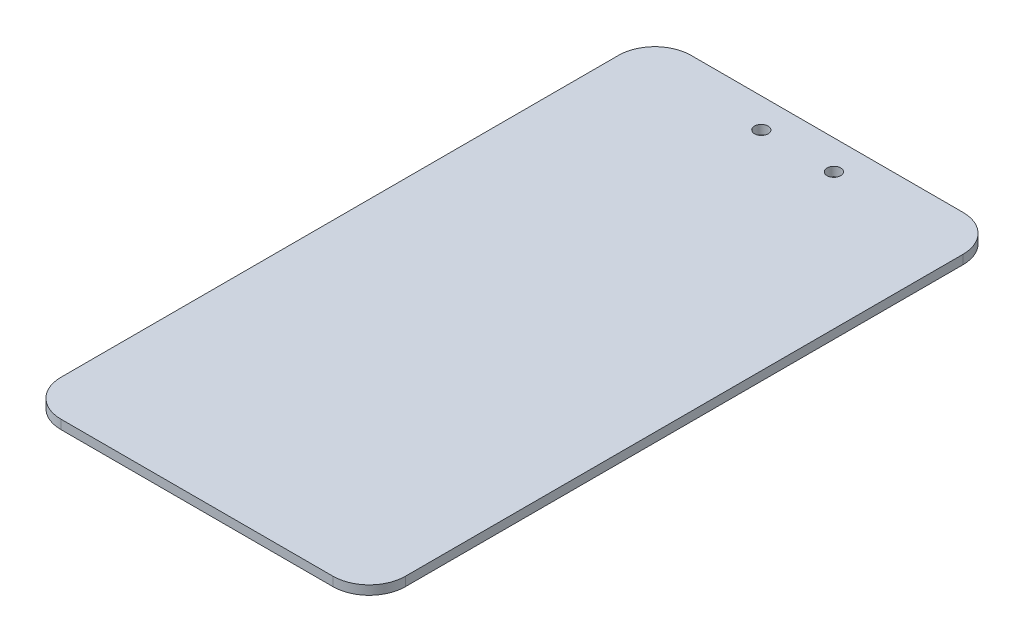
SolidWorks part; units mm, degrees
ref_plane "Front Plane" through (0, 0, 0) normal (0, 0, 1) x (1, 0, 0)
ref_plane "Top Plane" through (0, 0, 0) normal (0, 1, 0) x (1, 0, 0)
ref_plane "Right Plane" through (0, 0, 0) normal (1, 0, 0) x (0, 0, -1)
sketch "Sketch1" plane through (0, 0, 0) normal (0, 1, 0) x (1, 0, 0)
  line L0 (0, 69.5) -> (76, 69.5) construction
  line L1 (8, 0) -> (68, 0)
  line L2 (0, 8) -> (0, 131)
  line L3 (8, 139) -> (68, 139)
  line L4 (76, 8) -> (76, 131)
  line L5 (38, 139) -> (38, 0) construction
  circle A0 centre (46, 132.5) radius 1.5
  circle A1 centre (30, 132.5) radius 1.5
  arc A2 (8, 0) -> (0, 8) centre (8, 8) cw
  arc A3 (68, 0) -> (76, 8) centre (68, 8) ccw
  arc A4 (68, 139) -> (76, 131) centre (68, 131) cw
  arc A5 (0, 131) -> (8, 139) centre (8, 131) cw
  point P15 (0, 0)
  point P18 (76, 0)
  point P23 (0, 139)
  dimension "D3" = 3
  dimension "D6" = 8
  dimension "D1" = 76
  dimension "D2" = 139
  dimension "D4" = 6.5
  dimension "D5" = 8
extrude "Boss-Extrude1" add sketch "Sketch1" along normal blind 2
